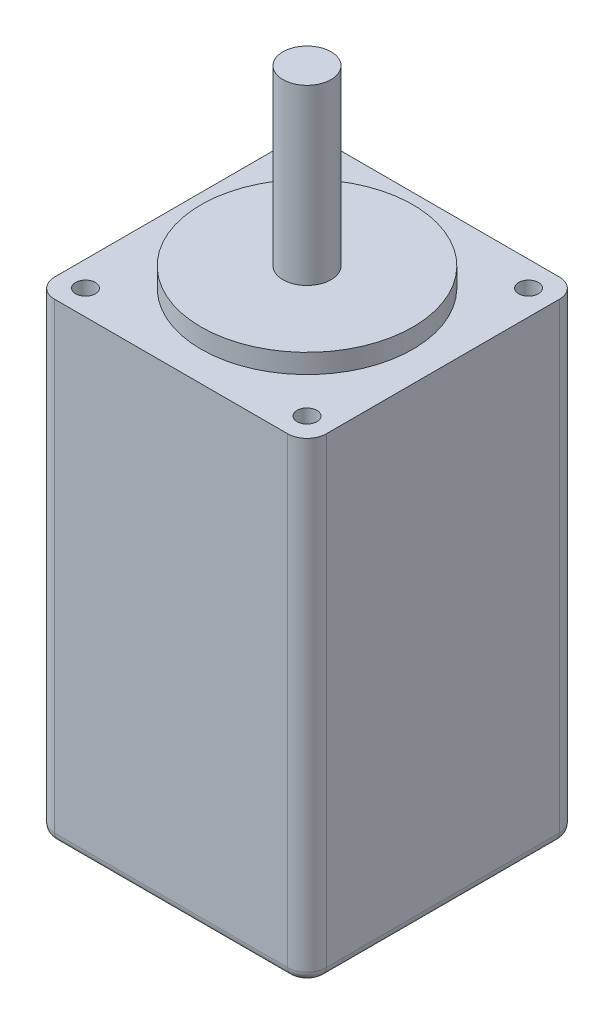
SolidWorks part; units mm, degrees
ref_plane "Front Plane" through (0, 0, 0) normal (0, 0, 1) x (1, 0, 0)
ref_plane "Top Plane" through (0, 0, 0) normal (0, 1, 0) x (1, 0, 0)
ref_plane "Right Plane" through (0, 0, 0) normal (1, 0, 0) x (0, 0, -1)
sketch "Sketch1" plane through (0, 0, 0) normal (0, 1, 0) x (1, 0, 0)
  line L1 (0, 0) -> (28.2, 0)
  line L2 (0, 0) -> (0, 28.2)
  line L3 (0, 28.2) -> (28.2, 28.2)
  line L4 (28.2, 0) -> (28.2, 28.2)
  dimension "D1" = 28.2
extrude "Boss-Extrude1" add sketch "Sketch1" along normal blind 49
sketch "Sketch2" plane through (0, 49, 0) normal (0, 1, 0) x (1, 0, 0)
  line L0 (28.2, 0) -> (28.2, 28.2) construction
  line L1 (0, 0) -> (28.2, 0) construction
  circle A0 centre (14.1, 14.1) radius 11
  point P5 (28.2, 14.1)
  point P9 (14.1, 0)
  dimension "D1" = 22
extrude "Boss-Extrude2" add sketch "Sketch2" along normal blind 2
sketch "Sketch3" plane through (0, 51, 0) normal (0, 1, 0) x (1, 0, 0)
  circle A0 centre (14.1, 14.1) radius 2.5
extrude "Boss-Extrude3" add sketch "Sketch3" along normal blind 18
fillet "Fillet1" radius 2 4 edges at (28.2, 24.5, -28.2) (0, 24.5, -28.2) (28.2, 24.5, 0) (0, 24.5, 0)
hole_wizard "Tap Drill for M2.5 Tap1" positions "Sketch4" profile "Sketch5" hole size "M2.5" standard "ISO"
sketch "Sketch4" plane through (0, 49, 0) normal (0, 1, 0) x (1, 0, 0)
  line L4 (0, 14.1) -> (28.2, 14.1) construction
  line L5 (0, 26.2) -> (0, 2) construction
  line L6 (28.2, 2) -> (28.2, 26.2) construction
  line L8 (14.1, 28.2) -> (14.1, 0) construction
  line L9 (26.2, 28.2) -> (2, 28.2) construction
  line L10 (2, 0) -> (26.2, 0) construction
  point P0 (2.6, 2.6)
  point P2 (25.6, 2.6)
  point P4 (25.6, 25.6)
  point P6 (2.6, 25.6)
  dimension "D1" = 23
  dimension "D2" = 23
sketch "Sketch5" plane through (2.6, 49, -2.6) normal (1, 0, 0) x (0, 0, 1)
  line L0 (0, 0) -> (0, 5.1159)
  line L1 (0, 5.1159) -> (1.025, 4.5)
  line L2 (1.025, 4.5) -> (1.025, 0)
  line L5 (1.025, 0) -> (0, 0)
  line L10 (0, 5.1159) -> (-1.025, 4.5) construction
  line L11 (0, -6.35) -> (0, 107.95) construction
  dimension "Hole Dia." = 2.05
  dimension "Hole Depth" = 4.5
  dimension "Drill Angle" = 118
fillet "Fillet2" radius 1 8 edges at (0.5858, 0, -0.5858) (0, 0, -14.1) (0.5858, 0, -27.6142) (14.1, 0, -28.2) (27.6142, 0, -27.6142) (28.2, 0, -14.1) (27.6142, 0, -0.5858) (14.1, 0, 0)
